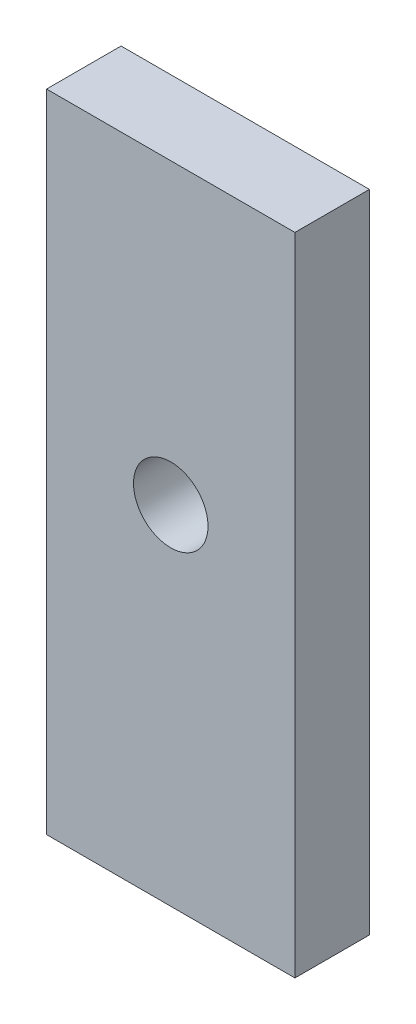
SolidWorks part; units mm, degrees
ref_plane "Спереди" through (0, 0, 0) normal (0, 0, 1) x (1, 0, 0)
ref_plane "Сверху" through (0, 0, 0) normal (0, 1, 0) x (1, 0, 0)
ref_plane "Справа" through (0, 0, 0) normal (1, 0, 0) x (0, 0, -1)
other "Configuration Table"
sketch "Эскиз1" plane through (0, 0, 0) normal (0, 0, 1) x (1, 0, 0)
  line L0 (5, 26) -> (5, 0) construction
  line L1 (0, 0) -> (10, 0)
  line L2 (0, 0) -> (0, 26)
  line L3 (0, 26) -> (10, 26)
  line L4 (10, 0) -> (10, 26)
  line L5 (0, 13) -> (10, 13) construction
  dimension "D1" = 10
  dimension "D2" = 26
extrude "Бобышка-Вытянуть1" add sketch "Эскиз1" along normal blind 3
sketch "Эскиз2" plane through (0, 0, 3) normal (0, 0, 1) x (1, 0, 0)
  line L0 (0, 0) -> (10, 0) construction
  line L1 (0, 26) -> (0, 0) construction
  circle A0 centre (5, 14) radius 1.5
  dimension "D1" = 3
  dimension "D2" = 14
  dimension "D3" = 5
extrude "Вырез-Вытянуть1" cut sketch "Эскиз2" against normal through all
